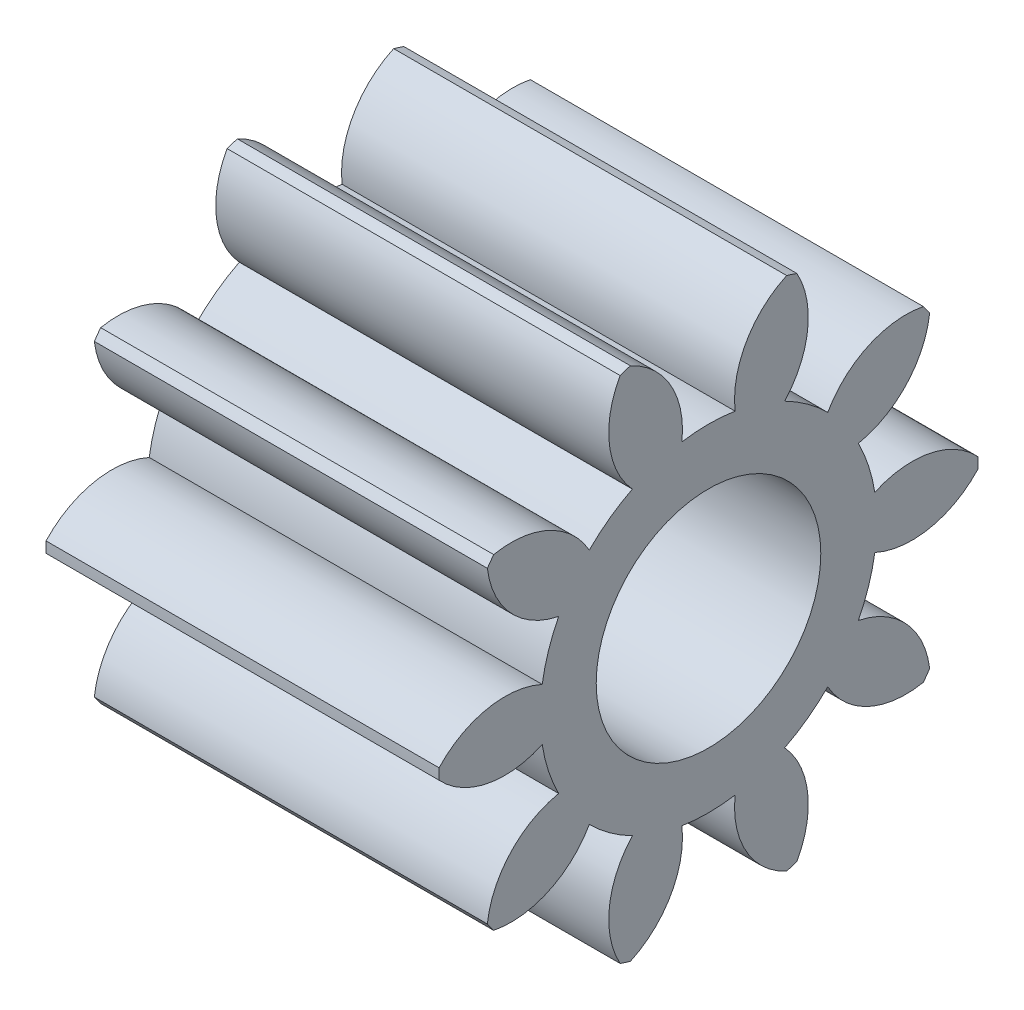
SolidWorks part; units mm, degrees
ref_plane "Plane1" through (0, 0, 0) normal (0, 0, 1) x (1, 0, 0)
ref_plane "Plane2" through (0, 0, 0) normal (0, 1, 0) x (1, 0, 0)
ref_plane "Plane3" through (0, 0, 0) normal (1, 0, 0) x (0, 0, -1)
sketch "HoldingSke" plane through (0, 0, 0) normal (0, 1, 0) x (1, 0, 0)
  line L0 (0, 0) -> (2.462, -0.4341)
  line L1 (-15, 0) -> (100, 0) construction
  line L2 (0, 0) -> (-2.1039, 2.3779)
  line L3 (0, 0) -> (-11.863, 4.5341)
  line L4 (0, 0) -> (8.5048, 1.4996)
  line L5 (0, 0) -> (-46.8476, -17.4728)
  line L6 (0, 0) -> (-2.9014, -1.9576)
  line L7 (-2.1039, 2.3779) -> (8.6586, 51.2059)
  line L8 (-76.2, 54.61) -> (-75.9, 54.61)
  line L9 (-71.009, 38.7566) -> (-53.1078, 45.2721)
  line L10 (-76.2, 71.12) -> (104.1128, 71.12)
  line L11 (0, 0) -> (-3.5, 0)
  line L12 (-76.2, 101.6) -> (-76.185, 101.6)
  line L13 (24.9733, 27.94) -> (52.9518, 28.4284)
  line L14 (24.9733, 27.94) -> (24.9743, 27.94)
  line L15 (24.9733, 27.94) -> (100.4006, 29.5858)
  line L16 (-63.627, -0.4) -> (-12.827, -0.4)
  circle A0 centre (0, 0) radius 1
  circle A1 centre (0, 0) radius 1.499
  circle A2 centre (0, 0) radius 37.5
  circle A3 centre (0, 0) radius 1
  dimension "MHD" = 2.998
  dimension "Hub_dia" = 75
  dimension "Bore" = 2
  dimension "MBD" = 2
  dimension "Num_teeth" = 10
  dimension "Pitch" = 2.5
  dimension "Overall_len" = 50
  dimension "Show_teeth" = 10
  dimension "Thickness" = 3.5
  dimension "OAL" = 50.0001
  dimension "T_dim" = 0.3
  dimension "Ap" = 20
  dimension "H" = 19.05
  dimension "Pitch_radius" = 180.3128
  dimension "Width" = 3.5
  dimension "Backlash" = 0.015
  dimension "Addendum_fac" = 1
  dimension "Dedendum_fac" = 1.25
  dimension "Clearance_fac" = 0.25
  dimension "Dedendum_add" = 0.001
  dimension "Module" = 0.4
sketch "BasProSke" plane through (0, 0, 0) normal (0, 1, 0) x (1, 0, 0)
  line L0 (-10, 0) -> (60, 0) construction
  line L1 (0, 0) -> (0, 2.4)
  line L2 (0, 0) -> (3.5, 0)
  line L3 (3.5, 0) -> (3.5, 2.4)
  line L4 (3.5, 2.4) -> (0, 2.4)
  dimension "Thickness" = 3.5
  dimension "Diameter" = 4.8
revolve "Base-Revolve" add sketch "BasProSke" angle 360 about L0
sketch "TooCutSke" plane through (0, 0, 0) normal (1, 0, 0) x (0, 0, -1)
  line L1 (0, 0) -> (0, 107) construction
  line L2 (0, 0) -> (-0.3391, 1.971) construction
  line L3 (0, 0) -> (-1.2233, 3.765) construction
  line L4 (-0.3391, 1.971) -> (-0.6117, 1.8825) construction
  arc A0 (0.2369, 1.4802) -> (-0.2369, 1.4802) centre (0, 0) ccw
  arc A1 (0.7316, 2.3124) -> (-0.7316, 2.3124) centre (0, 0) ccw
  circle A2 centre (0, 0) radius 2 construction
  circle A3 centre (0, 0) radius 1.8794 construction
  arc A4 (-0.2369, 1.4802) -> (-0.7316, 2.3124) centre (-1.0318, 1.5708) ccw
  arc A5 (0.7316, 2.3124) -> (0.2369, 1.4802) centre (1.0318, 1.5708) ccw
  dimension "Root_dia" = 2.998
  dimension "Overcut_dia" = 4.8508
  dimension "Pitch_dia" = 4
  dimension "Base_dia" = 3.7588
  dimension "Flank_rad" = 0.8
  dimension "Half_ang" = 18
  dimension "Half_CT" = 0.2866
extrude "ToothCut" cut sketch "TooCutSke" along normal through all
fillet "Breaks" [suppressed] radius 0.008
fillet "RootFillets" [suppressed] radius 0.101
pattern_circular "TeethCuts" count 10 every 36 about axis through (-10, 0, 0) along (1, 0, 0) of "ToothCut", "RootFillets", "Breaks"
sketch "HubNeaOneSke" plane through (0, 0, 0) normal (-1, 0, 0) x (0, 0, 1)
  circle A0 centre (0, 0) radius 1.499
  dimension "Diameter" = 2.998
extrude "HubNearOne" [suppressed] add sketch "HubNeaOneSke" along normal blind 46.5001
sketch "HubNeaBotSke" plane through (0, 0, 0) normal (-1, 0, 0) x (0, 0, 1)
  circle A0 centre (0, 0) radius 1.499
  dimension "Diameter" = 2.998
extrude "HubNearBoth" [suppressed] add sketch "HubNeaBotSke" along normal blind 23.25
ref_plane "FarPln" through (3.5, 0, 0) normal (1, 0, 0) x (0, 0, -1)
sketch "HubFarSke" plane through (3.5, 0, 0) normal (1, 0, 0) x (0, 0, -1)
  circle A0 centre (0, 0) radius 1.499
  dimension "Diameter" = 2.998
extrude "HubFar" [suppressed] add sketch "HubFarSke" along normal blind 23.25
sketch "BorSke" plane through (0, 0, 0) normal (1, 0, 0) x (0, 0, -1)
  circle A0 centre (0, 0) radius 1
  dimension "Diameter" = 2
extrude "Bore" cut sketch "BorSke" along normal mid plane 100.0001
sketch "KeySke" plane through (0, 0, 0) normal (1, 0, 0) x (0, 0, -1)
  line L0 (-0.4, 0) -> (-0.4, 1.3)
  line L1 (-0.4, 1.3) -> (0.4, 1.3)
  line L2 (0.4, 1.3) -> (0.4, 0)
  line L3 (0, 0) -> (0, 34) construction
  line L4 (-0.4, 0) -> (0.4, 0)
  dimension "Offset" = 1.3
  dimension "Width" = 0.8
extrude "Keyway" [suppressed] cut sketch "KeySke" along normal mid plane 100.0001
pattern_circular "Keyway2" [suppressed] count 2 every 90 about axis through (-10, 0, 0) along (1, 0, 0)
equation "' \"Module@HoldingSke\" = 6.35"
equation "' \"Num_teeth@HoldingSke\" = 12"
equation "' \"Ap@HoldingSke\" =  20"
equation "' \"Ap@HoldingSke\" = 20"
equation "' \"Width@HoldingSke\" = 0.5 * 25.4"
equation "' \"Hub_dia@HoldingSke\"= 1 * 25.4"
equation "' \"Hub_dia@HoldingSke\" = 1 * 25.4"
equation "' \"Overall_len@HoldingSke\" = 1.0 * 25.4"
equation "' \"Bore@HoldingSke\" = 0.75 * 25.4"
equation "' \"T_dim@HoldingSke\" = 0.1 * 25.4"
equation "' \"Width@KeySke\" = 0.25 * 25.4"
equation "' \"Show_teeth@HoldingSke\" = 13"
equation "' \"Backlash@HoldingSke\" = 0.009 * 25.4"
equation "' \"Addendum_fac@HoldingSke\" = 1.0"
equation "' \"Dedendum_fac@HoldingSke\" = 1.25"
equation "' \"Dedendum_add@HoldingSke\" = 0.00005 * 25.4"
equation "' \"Clearance_fac@HoldingSke\" = 0.25"
equation "\"Pitch@HoldingSke\" = 1 / \"Module@HoldingSke\""
equation "\"Overcut_dia@TooCutSke\" = (\"Num_teeth@HoldingSke\" + 2 * \"Addendum_fac@HoldingSke\") / \"Pitch@HoldingSke\" + 0.002 * 25.4"
equation "\"Pitch_dia@TooCutSke\" = \"Num_teeth@HoldingSke\" / \"Pitch@HoldingSke\""
equation "\"Base_dia@TooCutSke\" = \"Num_teeth@HoldingSke\" / \"Pitch@HoldingSke\" * cos((\"Ap@HoldingSke\"  * 3.14159265 / 180))"
equation "\"Root_dia@TooCutSke\" = (\"Num_teeth@HoldingSke\" + 2) / \"Pitch@HoldingSke\" - 2 * (\"Addendum_fac@HoldingSke\" + \"Dedendum_fac@HoldingSke\") / \"Pitch@HoldingSke\" - \"Dedendum_add@HoldingSke\" * 2"
equation "\"Half_ang@TooCutSke\" = 180 / \"Num_teeth@HoldingSke\""
equation "\"Half_CT@TooCutSke\" = \"Num_teeth@HoldingSke\" / \"Pitch@HoldingSke\" * sin((3.14159265 / 2 / \"Num_teeth@HoldingSke\")) / 2 - 7 * \"Backlash@HoldingSke\" / 4"
equation "\"Flank_rad@TooCutSke\" = \"Num_teeth@HoldingSke\" / \"Pitch@HoldingSke\" / 5"
equation "\"Radius@RootFillets\" = \"Clearance_fac@HoldingSke\" / \"Pitch@HoldingSke\" + \"Dedendum_add@HoldingSke\""
equation "\"Break_rad@Breaks\" = 0.02 / \"Pitch@HoldingSke\""
equation "\"Thickness@HoldingSke\" = \"Width@HoldingSke\""
equation "\"OAL@HoldingSke\" = \"Thickness@HoldingSke\""
equation "\"MHD@HoldingSke\" = (\"Num_teeth@HoldingSke\" + 2) / \"Pitch@HoldingSke\" - 2 * (\"Addendum_fac@HoldingSke\" + \"Dedendum_fac@HoldingSke\")  / \"Pitch@HoldingSke\" - \"Dedendum_add@HoldingSke\" * 2"
equation "\"MBD@HoldingSke\" = (\"Num_teeth@HoldingSke\" + 2) / \"Pitch@HoldingSke\" - 2 * (\"Addendum_fac@HoldingSke\" + \"Dedendum_fac@HoldingSke\")  / \"Pitch@HoldingSke\" - \"Dedendum_add@HoldingSke\" * 2 - 0.002 * 25.4"
equation "\"MHD@HoldingSke\" = ((sgn( \"MHD@HoldingSke\" - \"Hub_dia@HoldingSke\" )-1)*( \"MHD@HoldingSke\" - \"Hub_dia@HoldingSke\" ))/-2+ \"Hub_dia@HoldingSke\""
equation "\"MBD@HoldingSke\" = ((sgn( \"MBD@HoldingSke\" - \"Bore@HoldingSke\" )-1)*( \"MBD@HoldingSke\" - \"Bore@HoldingSke\" ))/-2+ \"Bore@HoldingSke\""
equation "\"OAL@HoldingSke\" = ((sgn( \"OAL@HoldingSke\" - \"Overall_len@HoldingSke\" )+1)*( \"OAL@HoldingSke\" - \"Overall_len@HoldingSke\" ))/2 + \"Overall_len@HoldingSke\" + 0.000002 * 25.4"
equation "\"Num_teeth@TeethCuts\" = int( \"Show_teeth@HoldingSke\" ) + 1"
equation "\"Num_teeth@TeethCuts\" = ((sgn( \"Num_teeth@TeethCuts\" - \"Num_teeth@HoldingSke\" )-1)*( \"Num_teeth@TeethCuts\" - \"Num_teeth@HoldingSke\" ))/-2+ \"Num_teeth@HoldingSke\""
equation "\"Num_teeth@TeethCuts\" = ((sgn( \"Num_teeth@TeethCuts\" - 2.0)+1)*( \"Num_teeth@TeethCuts\" - 2.0))/2 +2.0"
equation "\"Angle@TeethCuts\" = 360.0 / \"Num_teeth@HoldingSke\""
equation "\"Diameter@BasProSke\" = (\"Num_teeth@HoldingSke\" + 2 * \"Addendum_fac@HoldingSke\") / \"Pitch@HoldingSke\""
equation "\"Thickness@BasProSke\"  = \"Thickness@HoldingSke\""
equation "' \"Fillet_rad@BasProSke\" =  \"Thickness@HoldingSke\" * 0.05"
equation "' \"Fillet_rad@BasProSke\" = \"Thickness@HoldingSke\" * 0.05"
equation "\"MHD@HoldingSke\" = ((sgn( \"MHD@HoldingSke\" - \"Root_dia@TooCutSke\" )-1)*( \"MHD@HoldingSke\" - \"Root_dia@TooCutSke\" ))/-2+ \"Root_dia@TooCutSke\""
equation "\"Diameter@HubNeaOneSke\" = \"MHD@HoldingSke\""
equation "\"Length@HubNearOne\" = \"OAL@HoldingSke\" - \"Thickness@BasProSke\""
equation "\"Diameter@HubNeaBotSke\" = \"MHD@HoldingSke\""
equation "\"Length@HubNearBoth\" = ( \"OAL@HoldingSke\" - \"Thickness@BasProSke\" ) / 2.0"
equation "\"Thickness@FarPln\" = \"Thickness@BasProSke\""
equation "\"Diameter@HubFarSke\" = \"MHD@HoldingSke\""
equation "\"Length@HubFar\" = ( \"OAL@HoldingSke\" - \"Thickness@BasProSke\" ) / 2.0"
equation "\"Diameter@BorSke\" = \"MBD@HoldingSke\""
equation "\"D1@Bore\" = \"OAL@HoldingSke\" * 2.0"
equation "\"D1@Keyway\" = \"OAL@HoldingSke\" * 2.0"
equation "\"Offset@KeySke\" = \"T_dim@HoldingSke\" + \"MBD@HoldingSke\" / 2.0"
